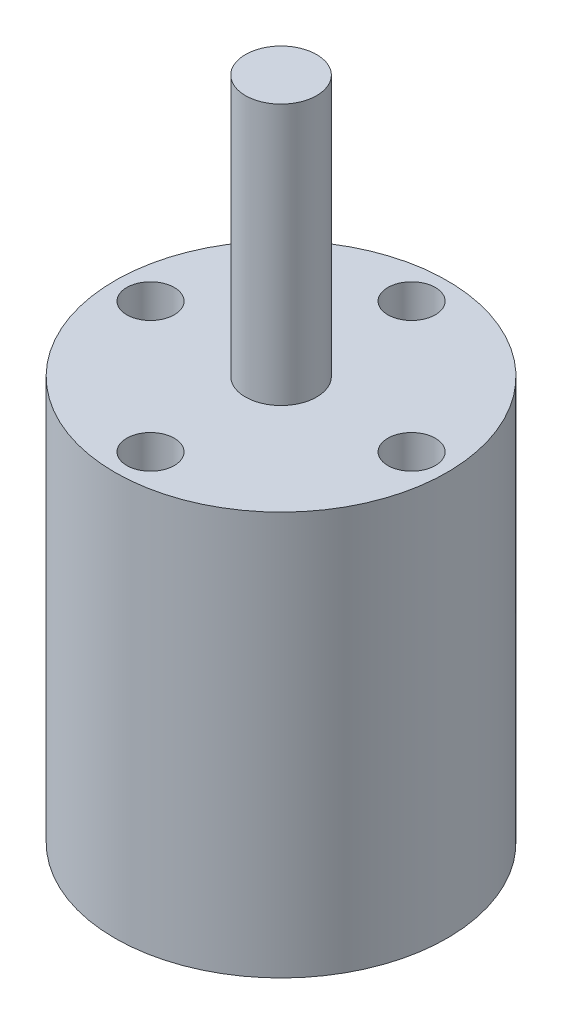
SolidWorks part; units mm, degrees
ref_plane "前视基准面" through (0, 0, 0) normal (0, 0, 1) x (1, 0, 0)
ref_plane "上视基准面" through (0, 0, 0) normal (0, 1, 0) x (1, 0, 0)
ref_plane "右视基准面" through (0, 0, 0) normal (1, 0, 0) x (0, 0, -1)
other "Configuration Table"
sketch "草图1" plane through (0, 0, 0) normal (0, 1, 0) x (1, 0, 0)
  circle A0 centre (0, 0) radius 7
  dimension "D1" = 14
extrude "凸台-拉伸1" add sketch "草图1" along normal blind 17
sketch "草图2" plane through (0, 17, 0) normal (0, 1, 0) x (1, 0, 0)
  line L0 (-7, 0) -> (7, 0) construction
  circle A0 centre (0, 0) radius 1.5
  circle A1 centre (5, 0) radius 1
  circle A2 centre (0, -5) radius 1
  circle A3 centre (-5, 0) radius 1
  circle A4 centre (0, 5) radius 1
  circle A5 centre (0, 0) radius 7 construction
  dimension "D1" = 3
  dimension "D2" = 2
  dimension "D4" = 5
  dimension "D3" = 4
extrude "凸台-拉伸3" add sketch "草图2" along normal blind 11 contours A0
sketch "草图4" plane through (0, 17, 0) normal (0, 1, 0) x (1, 0, 0)
  line L0 (-7, 0) -> (7, 0) construction
  line L1 (5.5, 0) -> (-5.5, 0) construction
  line L3 (0, -5.5) -> (0, 5.5) construction
  circle A3 centre (0, -5.5) radius 1
  circle A4 centre (0, 0) radius 7 construction
  circle A5 centre (-5.5, 0) radius 1
  circle A6 centre (0, 5.5) radius 1
  circle A7 centre (5.5, 0) radius 1
  point P0 (0, 0)
  dimension "D1" = 4
  dimension "D3" = 2
  dimension "D2" = 11
extrude "切除-拉伸1" cut sketch "草图4" against normal blind 5
